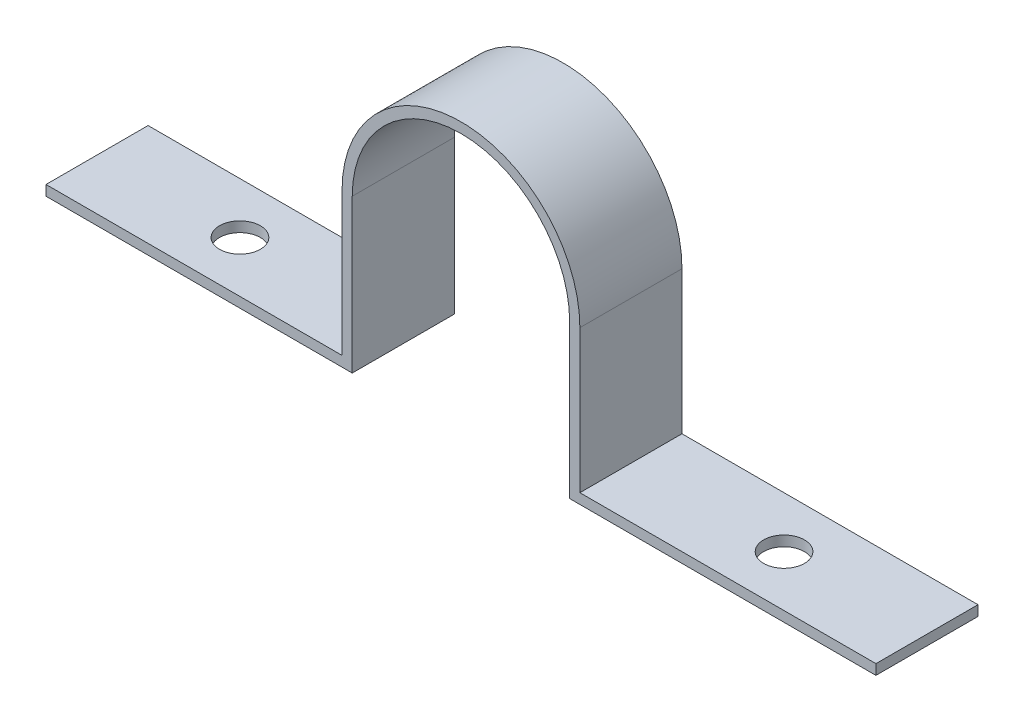
SolidWorks part; units mm, degrees
ref_plane "Alzado" through (0, 0, 0) normal (0, 0, 1) x (1, 0, 0)
ref_plane "Planta" through (0, 0, 0) normal (0, 1, 0) x (1, 0, 0)
ref_plane "Vista lateral" through (0, 0, 0) normal (1, 0, 0) x (0, 0, -1)
sketch "Croquis1" plane through (0, 0, 0) normal (0, 0, 1) x (1, 0, 0)
  line L7 (10.65, 0) -> (10.65, -15)
  line L17 (10.65, -15) -> (40.65, -15)
  line L18 (40.65, -15) -> (40.65, -14)
  line L25 (11.65, 0) -> (11.65, -14)
  line L26 (11.65, -14) -> (39.65, -14)
  line L30 (39.65, -14) -> (40.65, -14)
  line L31 (40.65, -15) -> (40.65, -13.8801) construction
  line L32 (0, 0) -> (0, -11.65) construction
  line L33 (-39.65, -14) -> (-40.65, -14)
  line L34 (-11.65, -14) -> (-39.65, -14)
  line L35 (-11.65, 0) -> (-11.65, -14)
  line L36 (39.65, -14) -> (39.65, -13.8801) construction
  line L37 (-40.65, -15) -> (-40.65, -14)
  line L38 (-10.65, -15) -> (-40.65, -15)
  line L39 (-10.65, 0) -> (-10.65, -15)
  arc A2 (10.65, 0) -> (-10.65, 0) centre (0, 0) ccw
  arc A5 (11.65, 0) -> (-11.65, 0) centre (0, 0) ccw
  dimension "D1" = 21.3
  dimension "D2" = 30
  dimension "D4" = 1
  dimension "D3" = 15
extrude "Saliente-Extruir1" add sketch "Croquis1" along normal blind 10
sketch "Croquis2" plane through (0, -16.5074, 0) normal (0, 1, 0) x (1, 0, 0)
  line L2 (-40.65, -10) -> (-40.65, 0) construction
  line L3 (11.65, -10) -> (11.65, 0) construction
  circle A0 centre (-26.65, -5) radius 2
  circle A1 centre (26.65, -5) radius 2
  point P6 (-40.65, -5)
  dimension "D1" = 15
  dimension "D3" = 4
  dimension "D4" = 4
  dimension "D2" = 15
extrude "Cortar-Extruir1" cut sketch "Croquis2" along normal blind 10
